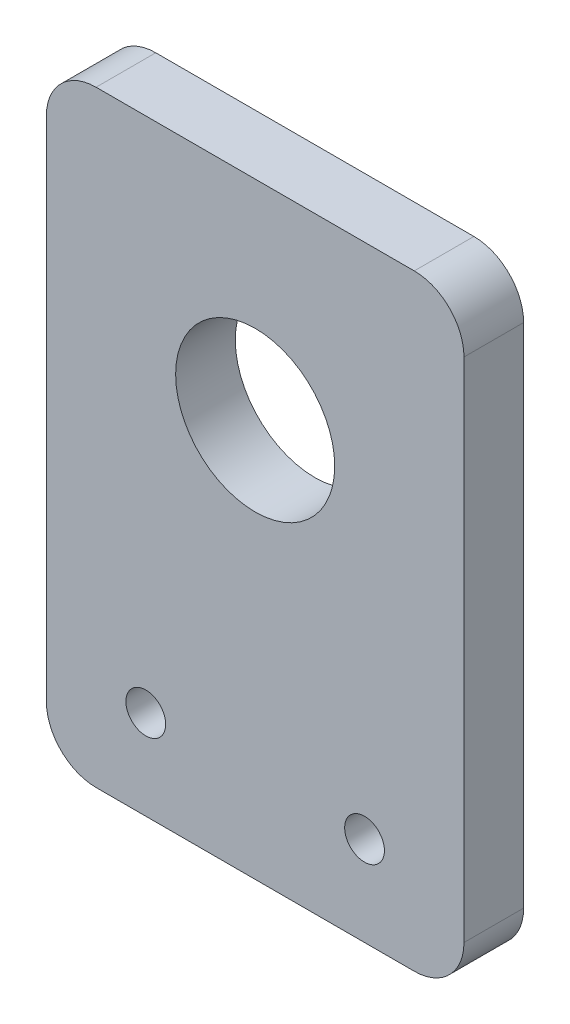
SolidWorks part; units mm, degrees
ref_plane "Front Plane" through (0, 0, 0) normal (0, 0, 1) x (1, 0, 0)
ref_plane "Top Plane" through (0, 0, 0) normal (0, 1, 0) x (1, 0, 0)
ref_plane "Right Plane" through (0, 0, 0) normal (1, 0, 0) x (0, 0, -1)
sketch "Sketch1" plane through (0, 0, 0) normal (0, 0, 1) x (1, 0, 0)
  line L1 (5, 0) -> (37, 0)
  line L2 (0, 5) -> (0, 56)
  line L3 (5, 61) -> (37, 61)
  line L4 (42, 5) -> (42, 56)
  line L5 (5.5, 24.5) -> (36.5, 24.5) construction
  line L6 (5.5, 24.5) -> (5.5, 55.5) construction
  line L7 (5.5, 55.5) -> (36.5, 55.5) construction
  line L8 (36.5, 24.5) -> (36.5, 55.5) construction
  line L9 (5.5, 24.5) -> (36.5, 55.5) construction
  line L10 (5.5, 55.5) -> (36.5, 24.5) construction
  circle A0 centre (21, 40) radius 8
  arc A5 (5, 0) -> (0, 5) centre (5, 5) cw
  arc A6 (37, 0) -> (42, 5) centre (37, 5) ccw
  arc A7 (37, 61) -> (42, 56) centre (37, 56) cw
  arc A8 (0, 56) -> (5, 61) centre (5, 56) cw
  circle A9 centre (10, 9) radius 2
  circle A10 centre (32, 9) radius 2
  point P18 (0, 0)
  point P23 (42, 61)
  point P26 (0, 61)
  dimension "D9" = 5
  dimension "D10" = 9
  dimension "D12" = 4
  dimension "D13" = 10
  dimension "D14" = 10
  dimension "D3" = 16
  dimension "D1" = 61
  dimension "D2" = 42
  dimension "D6" = 31
  dimension "D8" = 31
  dimension "D11" = 9
extrude "Boss-Extrude1" add sketch "Sketch1" along normal blind 6
